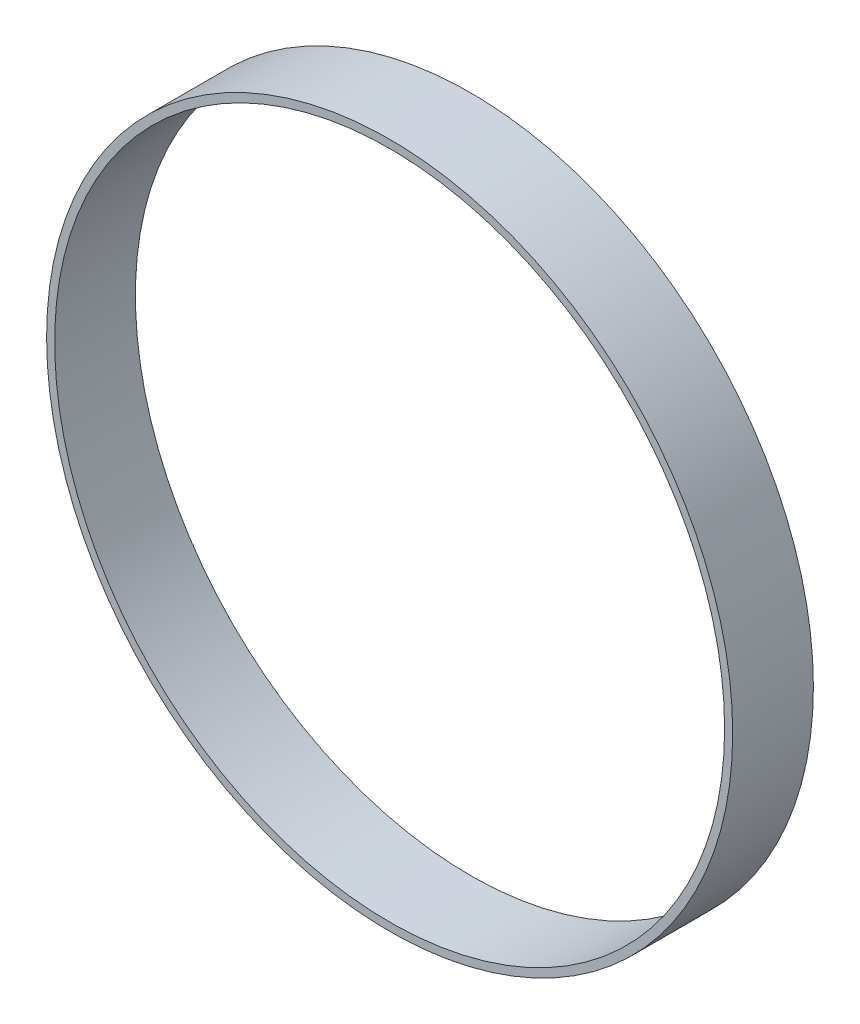
SolidWorks part; units mm, degrees
ref_plane "Front Plane" through (0, 0, 0) normal (0, 0, 1) x (1, 0, 0)
ref_plane "Top Plane" through (0, 0, 0) normal (0, 1, 0) x (1, 0, 0)
ref_plane "Right Plane" through (0, 0, 0) normal (1, 0, 0) x (0, 0, -1)
ref_plane "Plane1" through (0, 0, 0) normal (0, 0, 1) x (1, 0, 0)
sketch "Sketch1" plane through (0, 0, 0) normal (0, 0, 1) x (1, 0, 0)
  circle A0 centre (0, 0) radius 83
  circle A1 centre (0, 0) radius 85
extrude "Boss-Extrude1" add sketch "Sketch1" along normal blind 20
